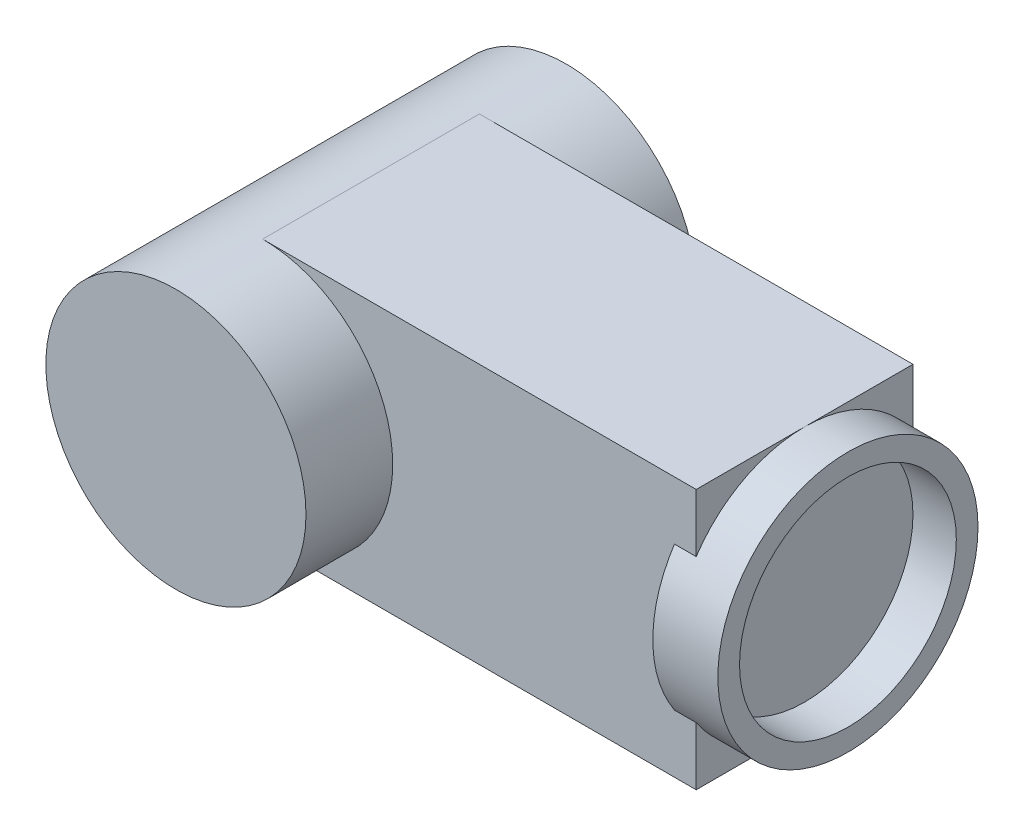
SolidWorks part; units mm, degrees
ref_plane "Front Plane" through (0, 0, 0) normal (0, 0, 1) x (1, 0, 0)
ref_plane "Top Plane" through (0, 0, 0) normal (0, 1, 0) x (1, 0, 0)
ref_plane "Right Plane" through (0, 0, 0) normal (1, 0, 0) x (0, 0, -1)
sketch "Sketch3" plane through (0, 0, 0) normal (0, 0, 1) x (1, 0, 0)
  line L1 (-50, -30) -> (50, -30)
  line L2 (-50, -30) -> (-50, 30)
  line L3 (-50, 30) -> (50, 30)
  line L4 (50, -30) -> (50, 30)
  line L5 (-50, -30) -> (50, 30) construction
  line L6 (-50, 30) -> (50, -30) construction
  point P0 (0, 0)
  dimension "D1" = 100
  dimension "D2" = 60
extrude "Boss-Extrude3" add sketch "Sketch3" along normal mid plane 50
sketch "Sketch4" plane through (0, 0, 0) normal (0, 0, 1) x (1, 0, 0)
  line L0 (-50, 30) -> (-50, -30) construction
  circle A0 centre (-50, 0) radius 30
  dimension "D1" = 0
extrude "Boss-Extrude5" add sketch "Sketch4" along normal mid plane 90
sketch "Sketch5" plane through (50, 0, 0) normal (1, 0, 0) x (0, 0, -1)
  circle A0 centre (0, 0) radius 30
  circle A1 centre (0, 0) radius 25
  line M1 (25, -30) -> (25, 30)
  line M3 (-25, 30) -> (-25, -30)
extrude "Boss-Extrude9" add sketch "Sketch5" along normal blind 10 and the other way blind 5 contours A0 M3 | A1 A0 M1 M3 | A0 M1 | A1 A0 M3 M1
